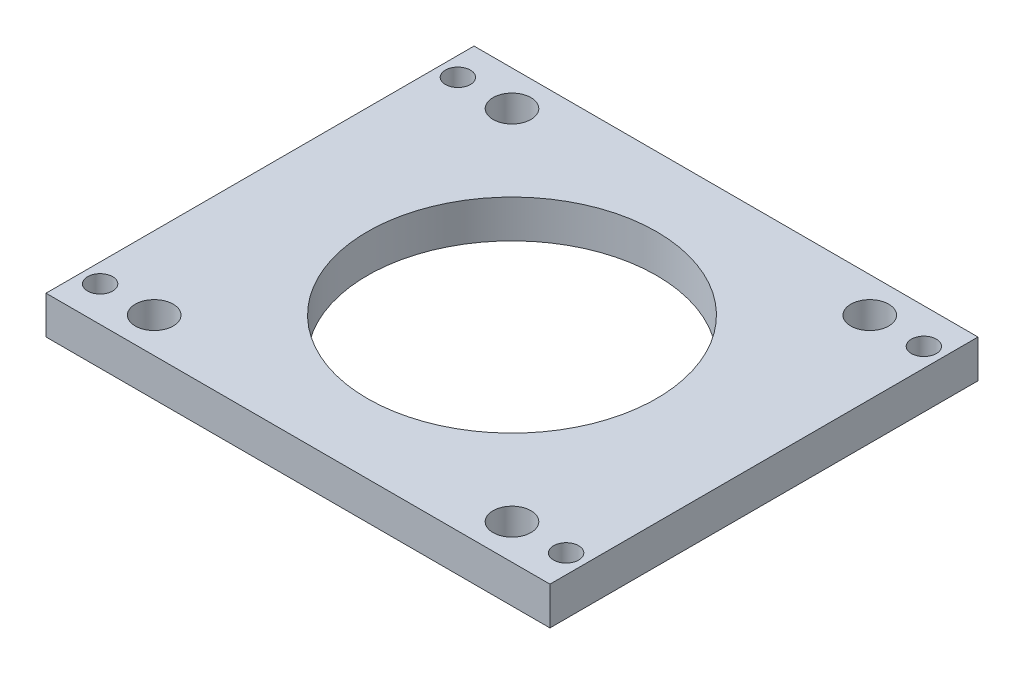
SolidWorks part; units mm, degrees
ref_plane "Płaszczyzna przednia" through (0, 0, 0) normal (0, 0, 1) x (1, 0, 0)
ref_plane "Płaszczyzna górna" through (0, 0, 0) normal (0, 1, 0) x (1, 0, 0)
ref_plane "Płaszczyzna prawa" through (0, 0, 0) normal (1, 0, 0) x (0, 0, -1)
sketch "Szkic1" plane through (0, 0, 0) normal (0, 1, 0) x (1, 0, 0)
  line L0 (33.2, 56.4) -> (33.2, 0) construction
  line L1 (0, 0) -> (66.4, 0)
  line L2 (0, 0) -> (0, 56.4)
  line L3 (0, 56.4) -> (66.4, 56.4)
  line L4 (66.4, 0) -> (66.4, 56.4)
  line L5 (0, 28.2) -> (66.4, 28.2) construction
  line L6 (5, 56.4) -> (5, 0) construction
  line L7 (61.4, 56.4) -> (61.4, 0) construction
  line L8 (66.4, 51.77) -> (0, 51.77) construction
  line L9 (66.4, 4.63) -> (0, 4.63) construction
  circle A0 centre (33.2, 28.2) radius 19.05
  circle A1 centre (9.63, 51.77) radius 2.5
  circle A2 centre (56.77, 51.77) radius 2.5
  circle A3 centre (56.77, 4.63) radius 2.5
  circle A4 centre (9.63, 4.63) radius 2.5
  point P27 (2.5, 51.77)
  point P28 (63.9, 51.77)
  point P29 (63.9, 4.63)
  point P30 (2.5, 4.63)
  dimension "D3" = 38.1
  dimension "D4" = 47.14
  dimension "D5" = 47.14
  dimension "D1" = 66.4
  dimension "D2" = 56.4
  dimension "D6" = 28.2
  dimension "D7" = 2.5
extrude "Dodanie-wyciągnięcie1" add sketch "Szkic1" along normal blind 5
sketch "Szkic3" plane through (0, 5, 0) normal (0, 1, 0) x (1, 0, 0)
  point P0 (2.5, 51.77)
  point P1 (63.9, 51.77)
  point P3 (63.9, 4.63)
  point P5 (2.5, 4.63)
  point P10 (2.5, 4.63)
hole_wizard "Otwór gwintowany M41" positions "Szkic 3D4" profile "Szkic5" tap size "M4" standard "ISO" end condition through all
sketch3d "Szkic 3D4"
  point P0 (2.5, 5, -51.77)
sketch "Szkic5" plane through (2.5, 5, -51.77) normal (1, 0, 0) x (0, 0, 1)
  line L0 (0, 0) -> (0, 5)
  line L1 (0, 5) -> (1.65, 5)
  line L2 (1.65, 5) -> (1.65, 0)
  line L5 (1.65, 0) -> (0, 0)
  line L11 (0, -6.35) -> (0, 107.95) construction
  dimension "Średnica otworu gwintowanego na wylot" = 3.3
  dimension "Głębokość otworu gwintowanego na wylot" = 5
cosmetic thread "Gwint otworu1" parameters "D2"=4
hole_wizard "Otwór gwintowany M42" positions "Szkic 3D5" profile "Szkic6" tap size "M4" standard "ISO" end condition through all
sketch3d "Szkic 3D5"
  point P0 (63.9, 5, -51.77)
  point P3 (63.9, 5, -4.63)
  point P6 (2.5, 5, -4.63)
sketch "Szkic6" plane through (63.9, 5, -51.77) normal (1, 0, 0) x (0, 0, 1)
  line L0 (0, 0) -> (0, 5)
  line L1 (0, 5) -> (1.65, 5)
  line L2 (1.65, 5) -> (1.65, 0)
  line L5 (1.65, 0) -> (0, 0)
  line L11 (0, -6.35) -> (0, 107.95) construction
  dimension "Średnica otworu gwintowanego na wylot" = 3.3
  dimension "Głębokość otworu gwintowanego na wylot" = 5
cosmetic thread "Gwint otworu2" parameters "D2"=4
cosmetic thread "Gwint otworu3" parameters "D2"=4
cosmetic thread "Gwint otworu4" parameters "D2"=4
